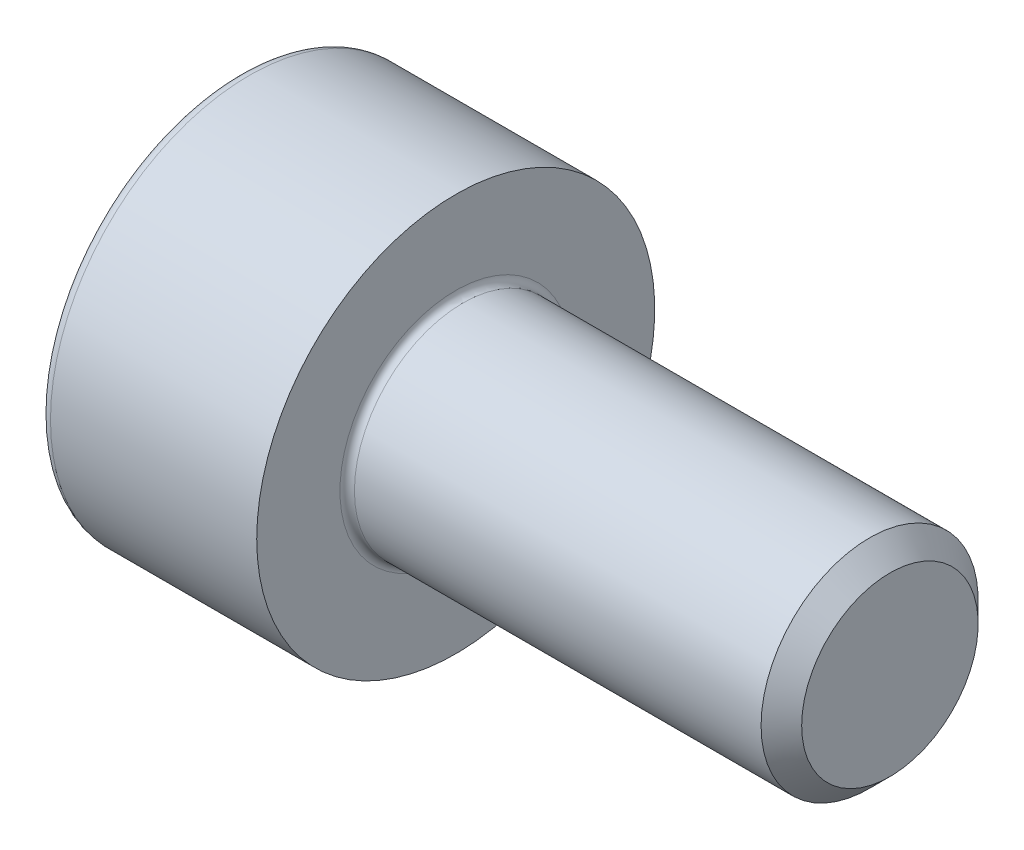
SolidWorks part; units mm, degrees
ref_plane "Plane1" through (0, 0, 0) normal (0, 0, 1) x (1, 0, 0)
ref_plane "Plane2" through (0, 0, 0) normal (0, 1, 0) x (1, 0, 0)
ref_plane "Plane3" through (0, 0, 0) normal (1, 0, 0) x (0, 0, -1)
revolve "Base-Revolve" add sketch "BodySke"
sketch "BodySke" plane through (0, 0, 0) normal (0, 0, 1) x (1, 0, 0)
  line L0 (0, 0) -> (0, 2.75)
  line L1 (0, 2.75) -> (3, 2.75)
  line L2 (3, 2.75) -> (3, 1.5)
  line L3 (3, 1.5) -> (8.7195, 1.5)
  line L4 (9, 1.2195) -> (9, 0)
  line L5 (9, 0) -> (0, 0)
  line L6 (-31.75, 0) -> (127, 0) construction
  line L8 (9, 1.2195) -> (8.7195, 1.5)
  line L10 (9, -1.2195) -> (8.7195, -1.5) construction
  line L11 (3.5, 9.525) -> (3.5, 3.175) construction
  line L12 (3, 9.525) -> (3, 3.175) construction
  line L13 (-51, 9.525) -> (-51, 3.175) construction
  dimension "Diameter" = 3
  dimension "Head_ht" = 3
  dimension "Length" = 6
  dimension "Body_ch_ang" = 45
  dimension "Head_dia" = 5.5
  dimension "Minor_dia" = 2.439
  dimension "Advance" = 0.5
  dimension "Thread_nom" = 6
  dimension "Thread_length" = 60
cosmetic thread "ThreadCosmetic" [suppressed]
fillet "Fillet1" radius 0.1 1 edges at (3, 0, 1.5)
fillet "Fillet2" radius 0.15 1 edges at (0, 0, 2.75)
sketch "Sketch2" plane through (0, 0, 0) normal (0, 0, 1) x (1, 0, 0)
  line L0 (0, 1.28) -> (1.3, 1.28)
  line L1 (1.3, 1.28) -> (2.039, 0)
  line L2 (-31.75, 0) -> (127, 0) construction
  line L3 (2.039, 0) -> (0, 0)
  line L4 (0, 0) -> (0, 1.28)
  line L6 (0, 0) -> (47.625, 0) construction
  dimension "D1" = 1.28
  dimension "D2" = 60
  dimension "Depth" = 1.3
revolve "Hex-PreBroach" cut sketch "Sketch2" angle 360 about L6
sketch "Sketch3" plane through (0, 0, 0) normal (-1, 0, 0) x (0, 0.5, 0.866)
  line L0 (0.739, 1.28) -> (-0.739, 1.28)
  line L1 (-0.739, 1.28) -> (-1.478, 0)
  line L2 (0.739, 1.28) -> (1.478, 0)
  line L3 (0.739, -1.28) -> (1.478, 0)
  line L4 (0.739, -1.28) -> (-0.739, -1.28)
  line L5 (-0.739, -1.28) -> (-1.478, 0)
  dimension "D1" = 1.28
  dimension "D2" = 1.28
  dimension "Hex_size" = 2.56
extrude "Hex" cut sketch "Sketch3" against normal blind 1.3
sketch "ThdSchSke" plane through (0, 0, 0) normal (0, 0, 1) x (1, 0, 0)
  line L0 (4.5, -1.2195) -> (4.3036, -1.5)
  line L1 (4.5, -1.2195) -> (4.6964, -1.5)
  line L2 (4.6964, -1.5) -> (4.6964, -1.875)
  line L3 (-3.175, 0) -> (5.1513, 0) construction
  line L4 (0, 2.6) -> (0, -2.6) construction
  line L5 (4.6964, -1.875) -> (4.3036, -1.875)
  line L6 (4.3036, -1.875) -> (4.3036, -1.5)
  dimension "Thread_minor" = 2.439
  dimension "Diameter" = 3
  dimension "Start" = 4.5
  dimension "SideAngle" = 55
  dimension "VeeAngle" = 70
  dimension "Overcut" = 3.75
revolve "ThreadSchematic" [suppressed] cut sketch "ThdSchSke" angle 360 about L3
pattern_linear "ThdSchPat" [suppressed]
equation "\"D2@Sketch3\" = \"Hex_size@Sketch3\" / 2"
equation "\"D1@Sketch3\" = \"Hex_size@Sketch3\" / 2"
equation "\"D1@Sketch2\" = \"Hex_size@Sketch3\" / 2"
equation "\"Thread_minor@ThreadCosmetic\"  =  \"Minor_dia@BodySke\""
equation "\"Depth@Sketch2\" =  \"Key_eng@Hex\""
equation "\"Thread_length@ThreadCosmetic\" = ((sgn( (\"Length@BodySke\" - \"Advance@BodySke\" * 3.0) - \"Thread_nom@BodySke\" )-1)*( (\"Length@BodySke\" - \"Advance@BodySke\" * 3.0) - \"Thread_nom@BodySke\" ))/-2+ \"Thread_nom@BodySke\""
equation "\"Thread_minor@ThdSchSke\" = \"Minor_dia@BodySke\""
equation "\"Diameter@ThdSchSke\" = \"Diameter@BodySke\""
equation "\"Overcut@ThdSchSke\" = \"Diameter@BodySke\" * 1.25"
equation "\"Start@ThdSchSke\" = \"Head_ht@BodySke\" + \"Length@BodySke\" - \"Thread_length@ThreadCosmetic\"  '---Non-countersunk---"
equation "\"Num_threads@ThdSchPat\" = int( \"Thread_length@ThreadCosmetic\" / \"Advance@BodySke\" + 0.999 )  + 1"
equation "\"Advance@ThdSchPat\" = \"Thread_length@ThreadCosmetic\" /  (\"Num_threads@ThdSchPat\" - 1) 'relax it"
equation "\"Num_threads@ThdSchPat\" = \"Num_threads@ThdSchPat\" - sgn( \"Num_threads@ThdSchPat\" - 1) '---chamfered tips only---"
